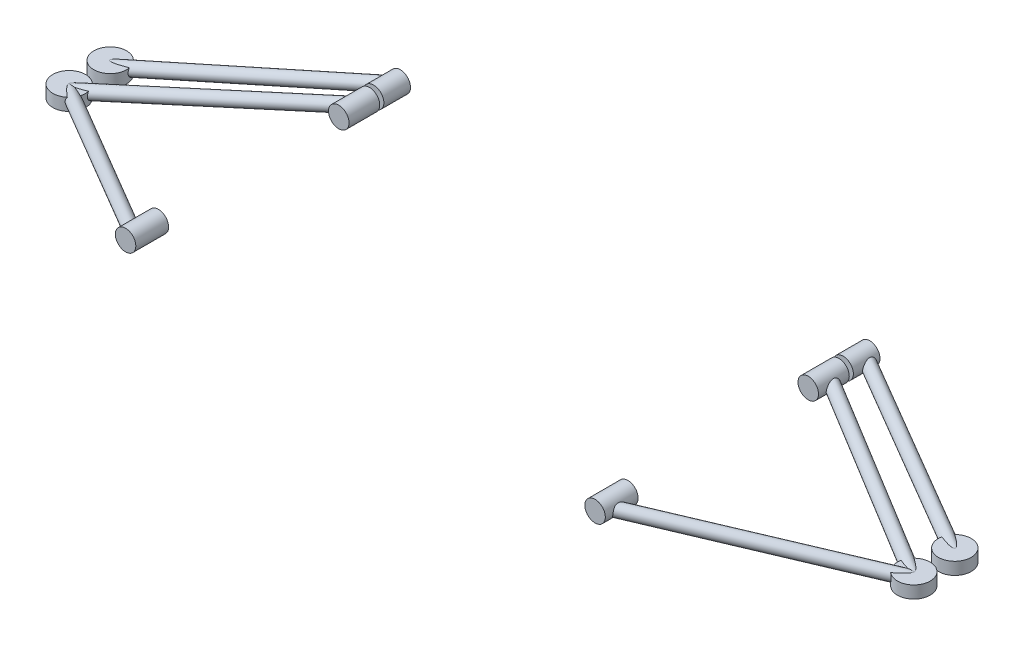
SolidWorks part; units mm, degrees
ref_plane "Front Plane" through (0, 0, 0) normal (0, 0, 1) x (1, 0, 0)
ref_plane "Top Plane" through (0, 0, 0) normal (0, 1, 0) x (1, 0, 0)
ref_plane "Right Plane" through (0, 0, 0) normal (1, 0, 0) x (0, 0, -1)
ref_plane "Plane4" through (0, 145.6371, 0) normal (0, 1, 0) x (1, 0, 0)
sketch "Sketch1" plane through (0, 145.6371, 0) normal (0, 1, 0) x (1, 0, 0)
  line L0 (515.0442, 1622.495) -> (515.0442, 1647.495) construction
  line L1 (515.0442, 1672.495) -> (515.0442, 1697.495) construction
  circle A0 centre (515.0442, 1684.995) radius 20
  circle A1 centre (515.0442, 1634.995) radius 20
  circle A2 centre (515.0442, 1634.995) radius 12.5
  circle A3 centre (515.0442, 1684.995) radius 12.5
  point P11 (515.0442, 1634.995)
  point P14 (515.0442, 1684.995)
  dimension "D1" = 40
  dimension "D2" = 40
  dimension "D3" = 25
  dimension "D4" = 25
sketch "Sketch2" plane through (0, 0, -1475) normal (0, 0, -1) x (-1, 0, 0)
  circle A0 centre (-286.3, 182.578) radius 12.5
  dimension "D1" = 25
extrude "Boss-Extrude1" add sketch "Sketch2" along normal up to surface (40 mm away)
sketch "Sketch3" plane through (0, 0, -1735) normal (0, 0, -1) x (-1, 0, 0)
  circle A0 centre (-286.3, 182.578) radius 12.5
  dimension "D1" = 25
extrude "Boss-Extrude2" add sketch "Sketch3" along normal up to surface (37.5 mm away) separate body
sketch "Sketch4" plane through (0, 0, -1777.5) normal (0, 0, -1) x (-1, 0, 0)
  circle A0 centre (-286.3, 182.578) radius 12.5
  dimension "D1" = 25
extrude "Boss-Extrude3" add sketch "Sketch4" along normal up to surface (32.5 mm away) separate body
extrude "Boss-Extrude4" add sketch "Sketch1" along normal mid plane 15 separate body contours A2 | A1 A2 | A3 | A0 A3
sketch3d "3DSketch2"
  line L0 (286.3, 182.578, -1475) -> (286.3, 182.578, -1515)
  line L1 (286.3, 182.578, -1515) -> (286.3, 182.578, -1475) construction
  line L2 (286.3, 182.578, -1470) -> (286.3, 182.578, -1475) construction
  line L3 (286.3, 182.578, -1735) -> (286.3, 182.578, -1772.5)
  line L4 (286.3, 182.578, -1772.5) -> (286.3, 182.578, -1735) construction
  line L5 (286.3, 182.578, -1730) -> (286.3, 182.578, -1735) construction
  line L6 (286.3, 182.578, -1777.5) -> (286.3, 182.578, -1810)
  line L7 (286.3, 182.578, -1810) -> (286.3, 182.578, -1777.5) construction
sketch3d "3DSketch3"
  line L0 (286.3, 182.578, -1485.2355) -> (515.0442, 145.6371, -1634.995)
  line L1 (286.3, 182.578, -1475) -> (286.3, 182.578, -1515) construction
  line L2 (515.0442, 145.6371, -1634.995) -> (286.3, 182.578, -1759.9218)
  line L3 (286.3, 182.578, -1735) -> (286.3, 182.578, -1772.5) construction
sweep "Sweep1" add path "3DSketch3" circular profile diameter 15 parameters "D3"=15
sketch3d "3DSketch4"
  line L0 (515.0442, 145.6371, -1684.995) -> (286.3, 182.578, -1803.7765)
  line L2 (286.3, 182.578, -1777.5) -> (286.3, 182.578, -1810) construction
sweep "Sweep2" add path "3DSketch4" circular profile diameter 15 parameters "D3"=15
mirror "Mirror1" about plane through (0, 0, 0) normal (1, 0, 0) of bodies 109 108
